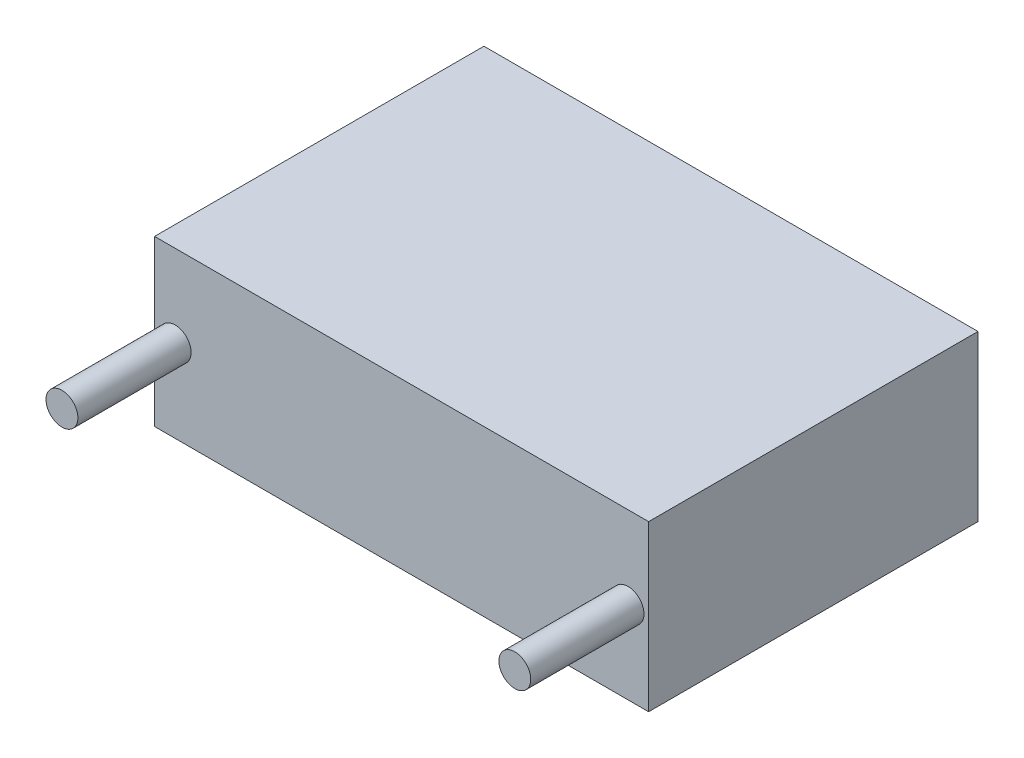
SolidWorks part; units mm, degrees
ref_plane "Спереди" through (0, 0, 0) normal (0, 0, 1) x (1, 0, 0)
ref_plane "Сверху" through (0, 0, 0) normal (0, 1, 0) x (1, 0, 0)
ref_plane "Справа" through (0, 0, 0) normal (1, 0, 0) x (0, 0, -1)
sketch "Эскиз1" plane through (0, 0, 0) normal (0, 0, 1) x (1, 0, 0)
  line L1 (0, 0) -> (24, 0)
  line L2 (0, 0) -> (0, 8)
  line L3 (0, 8) -> (24, 8)
  line L4 (24, 0) -> (24, 8)
  dimension "D1" = 8
  dimension "D2" = 24
extrude "Вытянуть1" add sketch "Эскиз1" along normal blind 16
sketch "Эскиз2" plane through (0, 0, 16) normal (0, 0, 1) x (1, 0, 0)
  line L0 (-0.6613, 4) -> (24.2043, 4) construction
  line L1 (0, 0) -> (24, 0) construction
  line L2 (24, 8) -> (0, 8) construction
  line L3 (12, 10.4113) -> (12, -0.9059) construction
  line L4 (0, 8) -> (0, 0) construction
  line L5 (24, 0) -> (24, 8) construction
  circle A0 centre (1, 4) radius 0.7746
  circle A1 centre (23, 4) radius 0.7746
  dimension "D1" = 22
extrude "Вытянуть2" add sketch "Эскиз2" along normal blind 5.5
